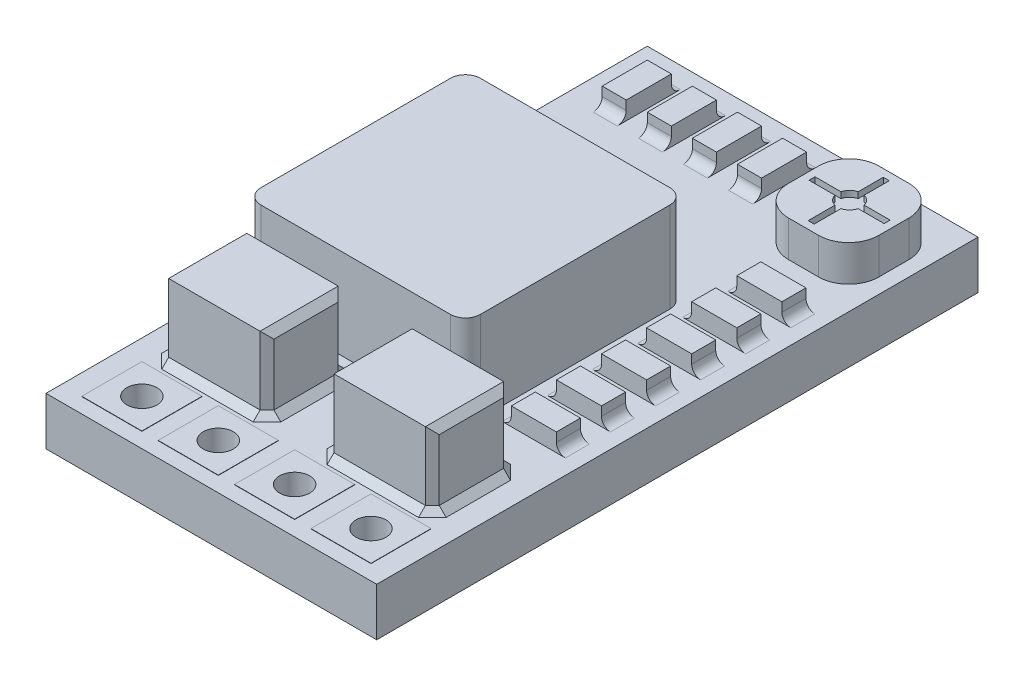
SolidWorks part; units mm, degrees
ref_plane "Front Plane" through (0, 0, 0) normal (0, 0, 1) x (1, 0, 0)
ref_plane "Top Plane" through (0, 0, 0) normal (0, 1, 0) x (1, 0, 0)
ref_plane "Right Plane" through (0, 0, 0) normal (1, 0, 0) x (0, 0, -1)
sketch "Sketch1" plane through (0, 0, 0) normal (0, 1, 0) x (1, 0, 0)
  line L1 (0, 0) -> (11, 0)
  line L2 (0, 0) -> (0, -20)
  line L3 (0, -20) -> (11, -20)
  line L4 (11, 0) -> (11, -20)
  dimension "D1" = 11
  dimension "D2" = 20
extrude "Boss-Extrude1" add sketch "Sketch1" along normal blind 1.6
sketch "Sketch2" plane through (0, 1.6, 0) normal (0, 1, 0) x (1, 0, 0)
  line L0 (0, 0) -> (0, -20) construction
  line L2 (0, -20) -> (11, -20) construction
  circle A0 centre (1.69, -18.5) radius 0.5
  circle A1 centre (4.23, -18.5) radius 0.5
  circle A2 centre (6.77, -18.5) radius 0.5
  circle A3 centre (9.31, -18.5) radius 0.5
  dimension "D1" = 1
  dimension "D3" = 1.69
  dimension "D4" = 1.5
  dimension "D2" = 4
extrude "Cut-Extrude1" cut sketch "Sketch2" against normal blind 1
sketch "Sketch3" plane through (0, 1.6, 0) normal (0, 1, 0) x (1, 0, 0)
  line L0 (3.23, -17.5) -> (5.23, -17.5)
  line L1 (0.69, -17.5) -> (2.69, -17.5)
  line L2 (0.69, -17.5) -> (0.69, -19.5)
  line L3 (0.69, -19.5) -> (2.69, -19.5)
  line L4 (2.69, -17.5) -> (2.69, -19.5)
  line L5 (3.23, -17.5) -> (3.23, -19.5)
  line L6 (3.23, -19.5) -> (5.23, -19.5)
  line L7 (5.23, -17.5) -> (5.23, -19.5)
  line L8 (5.77, -17.5) -> (7.77, -17.5)
  line L9 (5.77, -17.5) -> (5.77, -19.5)
  line L10 (5.77, -19.5) -> (7.77, -19.5)
  line L11 (7.77, -17.5) -> (7.77, -19.5)
  line L12 (8.31, -17.5) -> (10.31, -17.5)
  line L13 (8.31, -17.5) -> (8.31, -19.5)
  line L14 (8.31, -19.5) -> (10.31, -19.5)
  line L15 (10.31, -17.5) -> (10.31, -19.5)
  circle A0 centre (1.69, -18.5) radius 0.5 construction
  circle A1 centre (1.69, -18.5) radius 0.5
  circle A2 centre (4.23, -18.5) radius 0.5
  circle A3 centre (6.77, -18.5) radius 0.5
  circle A4 centre (9.31, -18.5) radius 0.5
  dimension "D7" = 1
  dimension "D1" = 2
  dimension "D2" = 2
  dimension "D3" = 1
  dimension "D4" = 1
  dimension "D5" = 4
  dimension "D6" = 4
extrude "Boss-Extrude2" add sketch "Sketch3" against normal blind 1.01 and the other way blind 0.01
sketch "Sketch4" plane through (0, 1.6, 0) normal (0, 1, 0) x (1, 0, 0)
  line L0 (5.5, 0) -> (5.5, -20) construction
  line L1 (1, -14.55) -> (4.5, -14.55)
  line L2 (1, -14.55) -> (1, -17.15)
  line L3 (1, -17.15) -> (4.5, -17.15)
  line L4 (4.5, -14.55) -> (4.5, -17.15)
  line L5 (11, 0) -> (0, 0) construction
  line L6 (0, -20) -> (11, -20) construction
  line L7 (0, 0) -> (0, -20) construction
  line L8 (6.5, -14.55) -> (6.5, -17.15)
  line L9 (10, -17.15) -> (6.5, -17.15)
  line L10 (10, -14.55) -> (10, -17.15)
  line L11 (10, -14.55) -> (6.5, -14.55)
  dimension "D1" = 3.5
  dimension "D2" = 2.6
  dimension "D3" = 2.85
  dimension "D4" = 1
extrude "Boss-Extrude3" add sketch "Sketch4" along normal blind 2.5
chamfer "Chamfer1" distance 0.23 angle 45 20 edges at (1, 2.85, 14.55) (1, 4.1, 15.85) (1, 2.85, 17.15) (1, 1.6, 15.85) (2.75, 1.6, 17.15) (2.75, 1.6, 14.55) (4.5, 2.85, 17.15) (4.5, 4.1, 15.85) (4.5, 2.85, 14.55) (4.5, 1.6, 15.85) (10, 2.85, 17.15) (10, 4.1, 15.85) (10, 2.85, 14.55) (10, 1.6, 15.85) (8.25, 1.6, 14.55) (8.25, 1.6, 17.15) (6.5, 2.85, 14.55) (6.5, 4.1, 15.85) (6.5, 2.85, 17.15) (6.5, 1.6, 15.85)
sketch "Sketch5" plane through (0, 1.6, 0) normal (0, 1, 0) x (1, 0, 0)
  line L0 (0, -20) -> (11, -20) construction
  line L1 (0.6501, -6.7) -> (7.9501, -6.7)
  line L2 (0.6501, -6.7) -> (0.6501, -14)
  line L3 (0.6501, -14) -> (7.9501, -14)
  line L4 (7.9501, -6.7) -> (7.9501, -14)
  dimension "D1" = 7.3
  dimension "D2" = 7.3
  dimension "D3" = 6
extrude "Boss-Extrude4" add sketch "Sketch5" along normal blind 3
sketch "Sketch7" plane through (0, 1.6, 0) normal (0, 1, 0) x (1, 0, 0)
  line L0 (0, 0) -> (0, -20) construction
  line L1 (1, -1) -> (1.8, -1)
  line L2 (1, -1) -> (1, -2.5)
  line L3 (1, -2.5) -> (1.8, -2.5)
  line L4 (1.8, -1) -> (1.8, -2.5)
  line L5 (11, 0) -> (0, 0) construction
  line L6 (2.5, -1) -> (3.3, -1)
  line L7 (2.5, -1) -> (2.5, -2.5)
  line L8 (2.5, -2.5) -> (3.3, -2.5)
  line L9 (3.3, -1) -> (3.3, -2.5)
  line L10 (4, -1) -> (4.8, -1)
  line L11 (4, -1) -> (4, -2.5)
  line L12 (4, -2.5) -> (4.8, -2.5)
  line L13 (4.8, -1) -> (4.8, -2.5)
  line L14 (5.5, -1) -> (6.3, -1)
  line L15 (5.5, -1) -> (5.5, -2.5)
  line L16 (5.5, -2.5) -> (6.3, -2.5)
  line L17 (6.3, -1) -> (6.3, -2.5)
  dimension "D1" = 0.8
  dimension "D2" = 1.5
  dimension "D3" = 1
  dimension "D4" = 1
  dimension "D5" = 4
extrude "Boss-Extrude5" add sketch "Sketch7" along normal blind 0.6
sketch "Sketch8" plane through (0, 1.6, 0) normal (0, 1, 0) x (1, 0, 0)
  line L1 (7.5, -0.8) -> (10.5, -0.8)
  line L2 (7.5, -0.8) -> (7.5, -3.8)
  line L3 (7.5, -3.8) -> (10.5, -3.8)
  line L4 (10.5, -0.8) -> (10.5, -3.8)
  line L5 (11, -20) -> (11, 0) construction
  line L6 (11, 0) -> (0, 0) construction
  dimension "D1" = 3
  dimension "D2" = 3
  dimension "D3" = 0.5
  dimension "D4" = 0.8
extrude "Boss-Extrude6" add sketch "Sketch8" along normal blind 1.2
sketch "Sketch9" plane through (0, 2.8, 0) normal (0, 1, 0) x (1, 0, 0)
  line L0 (10.5, -0.8) -> (7.5, -0.8) construction
  line L1 (8.9, -1.05) -> (9.1, -1.05)
  line L2 (8.9, -1.05) -> (8.9, -3.55)
  line L3 (8.9, -3.55) -> (9.1, -3.55)
  line L4 (9.1, -1.05) -> (9.1, -3.55)
  line L5 (9, -0.8) -> (9, -3.8) construction
  line L6 (7.5, -3.8) -> (10.5, -3.8) construction
  line L8 (7.75, -2.1718) -> (10.25, -2.1718)
  line L9 (7.75, -2.1718) -> (7.75, -2.3718)
  line L10 (7.75, -2.3718) -> (10.25, -2.3718)
  line L11 (10.25, -2.1718) -> (10.25, -2.3718)
  dimension "D1" = 0.2
  dimension "D2" = 2.5
  dimension "D3" = 0.25
  dimension "D4" = 0.1
  dimension "D5" = 0.2
  dimension "D6" = 2.5
  dimension "D7" = 1.15
extrude "Cut-Extrude4" cut sketch "Sketch9" against normal blind 0.2 contours L9 L10 L2 L8 | L11 L8 L4 L10
fillet "Fillet2" radius 1 4 edges at (7.5, 2.2, 0.8) (10.5, 2.2, 0.8) (10.5, 2.2, 3.8) (7.5, 2.2, 3.8)
sketch "Sketch11" plane through (0, 1.6, 0) normal (0, 1, 0) x (1, 0, 0)
  line L0 (11, -20) -> (11, 0) construction
  line L1 (8.7, -4.9236) -> (10.2, -4.9236)
  line L2 (8.7, -4.9236) -> (8.7, -5.7236)
  line L3 (8.7, -5.7236) -> (10.2, -5.7236)
  line L4 (10.2, -4.9236) -> (10.2, -5.7236)
  line L5 (8.7, -6.4236) -> (10.2, -6.4236)
  line L6 (8.7, -6.4236) -> (8.7, -7.2236)
  line L7 (8.7, -7.2236) -> (10.2, -7.2236)
  line L8 (10.2, -6.4236) -> (10.2, -7.2236)
  line L9 (8.7, -7.9236) -> (10.2, -7.9236)
  line L10 (8.7, -7.9236) -> (8.7, -8.7236)
  line L11 (8.7, -8.7236) -> (10.2, -8.7236)
  line L12 (10.2, -7.9236) -> (10.2, -8.7236)
  line L13 (8.7, -9.4236) -> (10.2, -9.4236)
  line L14 (8.7, -9.4236) -> (8.7, -10.2236)
  line L15 (8.7, -10.2236) -> (10.2, -10.2236)
  line L16 (10.2, -9.4236) -> (10.2, -10.2236)
  line L17 (8.7, -10.9236) -> (10.2, -10.9236)
  line L18 (8.7, -10.9236) -> (8.7, -11.7236)
  line L19 (8.7, -11.7236) -> (10.2, -11.7236)
  line L20 (10.2, -10.9236) -> (10.2, -11.7236)
  line L21 (8.7, -12.4236) -> (10.2, -12.4236)
  line L22 (8.7, -12.4236) -> (8.7, -13.2236)
  line L23 (8.7, -13.2236) -> (10.2, -13.2236)
  line L24 (10.2, -12.4236) -> (10.2, -13.2236)
  dimension "D1" = 1.5
  dimension "D2" = 0.8
  dimension "D3" = 0.8
  dimension "D4" = 6
extrude "Boss-Extrude7" add sketch "Sketch11" along normal blind 0.6
fillet "Fillet3" radius 0.3 20 edges at (8.7, 1.6, 5.3236) (8.7, 1.6, 6.8236) (8.7, 1.6, 8.3236) (8.7, 1.6, 9.8236) (8.7, 1.6, 11.3236) (8.7, 1.6, 12.8236) (10.2, 1.6, 12.8236) (10.2, 1.6, 11.3236) (10.2, 1.6, 9.8236) (10.2, 1.6, 8.3236) (10.2, 1.6, 6.8236) (10.2, 1.6, 5.3236) (5.9, 1.6, 2.5) (4.4, 1.6, 2.5) (2.9, 1.6, 2.5) (5.9, 1.6, 1) (4.4, 1.6, 1) (2.9, 1.6, 1) (1.4, 1.6, 1) (1.4, 1.6, 2.5)
sketch "Sketch12" plane through (0, 2.8, 0) normal (0, 1, 0) x (1, 0, 0)
  circle A0 centre (9, -2.2718) radius 0.4
  dimension "D1" = 0.8
extrude "Cut-Extrude5" cut sketch "Sketch12" against normal blind 0.2
sketch "Sketch13" plane through (0, 1.6, 0) normal (0, 1, 0) x (1, 0, 0)
  line L0 (11, 0) -> (0, 0) construction
  line L1 (1.6894, -4.5) -> (4.6894, -4.5)
  line L2 (1.6894, -4.5) -> (1.6894, -6)
  line L3 (1.6894, -6) -> (4.6894, -6)
  line L4 (4.6894, -4.5) -> (4.6894, -6)
  dimension "D1" = 1.5
  dimension "D2" = 3
  dimension "D3" = 4.5
extrude "Boss-Extrude8" add sketch "Sketch13" along normal blind 0.5
sketch "Sketch15" plane through (0, 1.6, 0) normal (0, 1, 0) x (1, 0, 0)
  line L0 (4.6894, -4.5) -> (1.6894, -4.5) construction
  line L1 (1.6894, -4.5) -> (1.9394, -4.5)
  line L2 (1.6894, -4.5) -> (1.6894, -3.9)
  line L3 (1.6894, -3.9) -> (1.9394, -3.9)
  line L4 (1.9394, -4.5) -> (1.9394, -3.9)
  line L5 (2.5994, -4.5) -> (2.8494, -4.5)
  line L6 (2.5994, -4.5) -> (2.5994, -3.9)
  line L7 (2.5994, -3.9) -> (2.8494, -3.9)
  line L8 (2.8494, -4.5) -> (2.8494, -3.9)
  line L9 (3.5094, -4.5) -> (3.7594, -4.5)
  line L10 (3.5094, -4.5) -> (3.5094, -3.9)
  line L11 (3.5094, -3.9) -> (3.7594, -3.9)
  line L12 (3.7594, -4.5) -> (3.7594, -3.9)
  line L13 (4.4194, -4.5) -> (4.6694, -4.5)
  line L14 (4.4194, -4.5) -> (4.4194, -3.9)
  line L15 (4.4194, -3.9) -> (4.6694, -3.9)
  line L16 (4.6694, -4.5) -> (4.6694, -3.9)
  line L17 (1.6894, -5.25) -> (4.6894, -5.25) construction
  line L18 (1.6894, -4.5) -> (1.6894, -6) construction
  line L19 (4.6894, -6) -> (4.6894, -4.5) construction
  line L20 (4.6694, -6) -> (4.6694, -6.6)
  line L21 (4.4194, -6.6) -> (4.6694, -6.6)
  line L22 (4.4194, -6) -> (4.4194, -6.6)
  line L23 (4.4194, -6) -> (4.6694, -6)
  line L24 (3.7594, -6) -> (3.7594, -6.6)
  line L25 (3.5094, -6.6) -> (3.7594, -6.6)
  line L26 (3.5094, -6) -> (3.5094, -6.6)
  line L27 (3.5094, -6) -> (3.7594, -6)
  line L28 (2.8494, -6) -> (2.8494, -6.6)
  line L29 (2.5994, -6.6) -> (2.8494, -6.6)
  line L30 (2.5994, -6) -> (2.5994, -6.6)
  line L31 (2.5994, -6) -> (2.8494, -6)
  line L32 (1.9394, -6) -> (1.9394, -6.6)
  line L33 (1.6894, -6.6) -> (1.9394, -6.6)
  line L34 (1.6894, -6) -> (1.6894, -6.6)
  line L35 (1.6894, -6) -> (1.9394, -6)
  dimension "D1" = 0.25
  dimension "D2" = 0.6
  dimension "D3" = 4
extrude "Boss-Extrude9" add sketch "Sketch15" along normal blind 0.2
fillet "Fillet4" radius 0.2 8 edges at (3.6344, 1.8, 6) (4.5444, 1.8, 6) (1.8144, 1.8, 6) (2.7244, 1.8, 6) (4.5444, 1.8, 4.5) (3.6344, 1.8, 4.5) (2.7244, 1.8, 4.5) (1.8144, 1.8, 4.5)
fillet "Скругление1" radius 0.5 4 edges at (0.6501, 3.1, 14) (0.6501, 3.1, 6.7) (7.9501, 3.1, 6.7) (7.9501, 3.1, 14)
